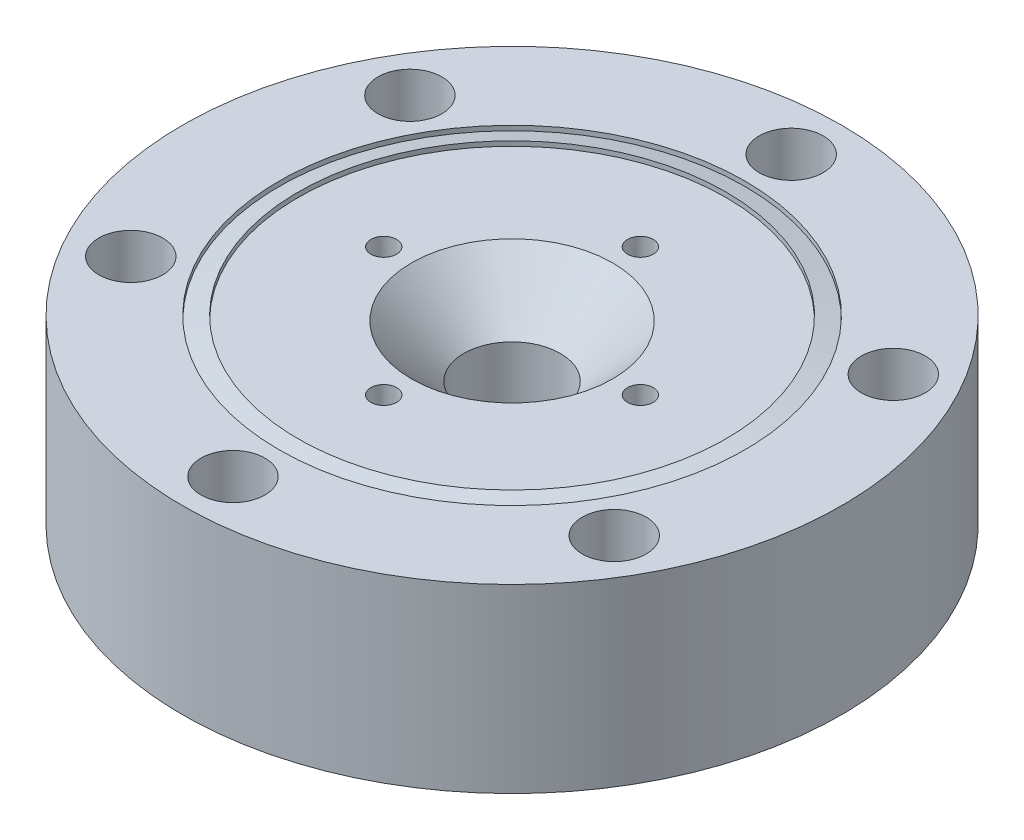
SolidWorks part; units mm, degrees
ref_plane "Front Plane" through (0, 0, 0) normal (0, 0, 1) x (1, 0, 0)
ref_plane "Top Plane" through (0, 0, 0) normal (0, 1, 0) x (1, 0, 0)
ref_plane "Right Plane" through (0, 0, 0) normal (1, 0, 0) x (0, 0, -1)
sketch "Sketch1" plane through (0, 0, 0) normal (0, 1, 0) x (1, 0, 0)
  circle A0 centre (0, 0) radius 34.671
  dimension "D1" = 69.342
extrude "Boss-Extrude1" add sketch "Sketch1" along normal blind 19.05
sketch "Sketch2" plane through (0, 0, 0) normal (0, -1, 0) x (1, 0, 0)
  point P0 (0, 0)
sketch "Sketch5" plane through (0, 0, 0) normal (0, -1, 0) x (1, 0, 0)
  circle A0 centre (0, 0) radius 5.08
  dimension "D1" = 10.16
extrude "Cut-Extrude1" cut sketch "Sketch5" against normal through all
chamfer "Chamfer1" distance 6 angle 45 1 edges at (0, 19.05, -5.08)
hole_wizard "#6-32 Tapped Hole1" positions "Sketch7" profile "Sketch6" tap size "#6-32" standard "Ansi Inch"
sketch "Sketch7" plane through (0, 19.05, 0) normal (0, 1, 0) x (-1, 0, 0)
  line L0 (0, -13.5) -> (0, 0) construction
  point P0 (0, -13.5)
  dimension "D1" = 13.5
sketch "Sketch6" plane through (0, 19.05, -13.5) normal (1, 0, 0) x (0, 0, 1)
  line L0 (0, 0) -> (0, 10.8127)
  line L1 (0, 10.8127) -> (1.3525, 10)
  line L2 (1.3525, 10) -> (1.3525, 0)
  line L5 (1.3525, 0) -> (0, 0)
  line L10 (0, 10.8127) -> (-1.3526, 10) construction
  line L11 (0, -6.35) -> (0, 107.95) construction
  dimension "Tap Drill Dia." = 2.7051
  dimension "Tap Drill Depth" = 10
  dimension "Drill Angle" = 118
cosmetic thread "Hole Thread1" parameters "D1"=7.01, "D2"=3.5052
pattern_circular "CirPattern1" count 4 over 360 about axis through (0, 0, 0) along (0, 1, 0) of "#6-32 Tapped Hole1"
sketch "Sketch8" plane through (0, 19.05, 0) normal (0, 1, 0) x (1, 0, 0)
  circle A0 centre (0, 29.3624) radius 3.3655
  dimension "D1" = 6.731
  dimension "D2" = 29.3624
extrude "Cut-Extrude2" cut sketch "Sketch8" against normal through all
pattern_circular "CirPattern2" count 6 over 360 about axis through (0, 0, 0) along (0, 1, 0) of "Cut-Extrude2"
sketch "Sketch9" plane through (0, 0, 0) normal (0, 0, 1) x (1, 0, 0)
  line L0 (0, -2.5708) -> (0, 0.5)
  line L1 (0, 0.5) -> (22.5, 0.5)
  line L2 (22.5, 0.5) -> (22.5, 0)
  line L3 (22.5, 0) -> (24.5, 0.5)
  line L4 (24.5, 0.5) -> (24.5, -7.988)
  line L5 (24.5, -7.988) -> (0, -7.988)
  line L6 (0, -7.988) -> (0, -2.5708)
  line L7 (-34.671, 0) -> (34.671, 0) construction
  dimension "D1" = 0.5
  dimension "D2" = 24.5
  dimension "D3" = 2
revolve "Cut-Revolve1" cut sketch "Sketch9" angle 360 about L0
ref_plane "Plane1" through (0, 9.525, 0) normal (0, -1, 0) x (1, 0, 0)
mirror "Mirror1" about plane through (0, 9.525, 0) normal (0, -1, 0) of "Cut-Revolve1"
